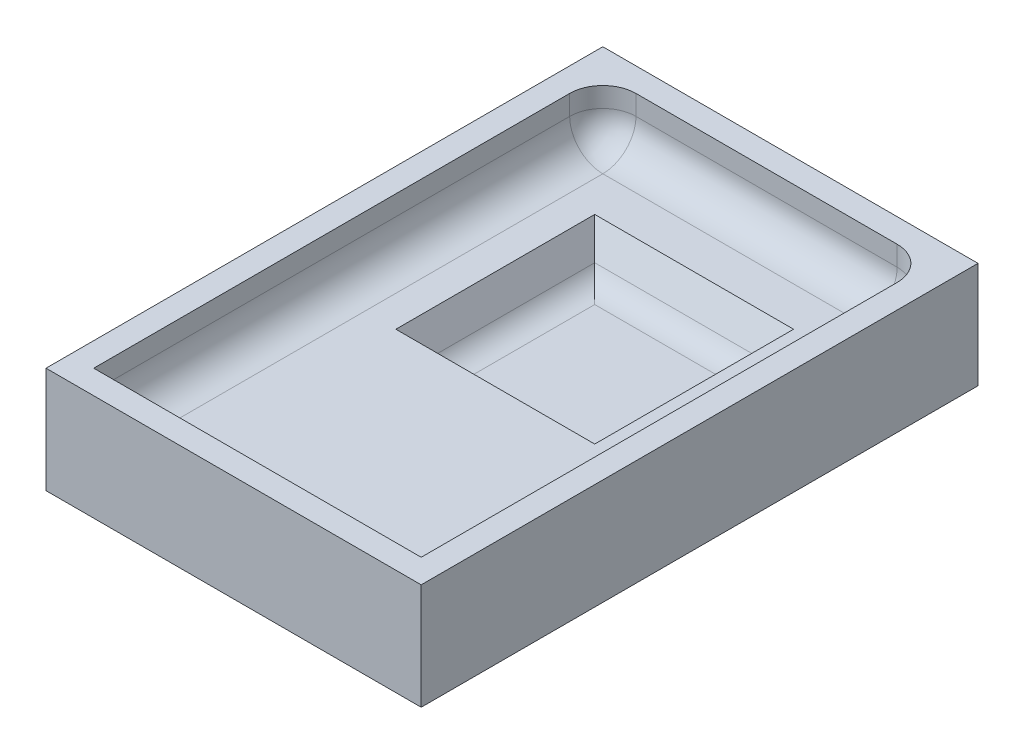
SolidWorks part; units mm, degrees
ref_plane "Front Plane" through (0, 0, 0) normal (0, 0, 1) x (1, 0, 0)
ref_plane "Top Plane" through (0, 0, 0) normal (0, 1, 0) x (1, 0, 0)
ref_plane "Right Plane" through (0, 0, 0) normal (1, 0, 0) x (0, 0, -1)
sketch "Sketch1" plane through (0, 0, 0) normal (0, 1, 0) x (1, 0, 0)
  line L1 (0, 0) -> (28.3, 0)
  line L2 (0, 0) -> (0, 42)
  line L3 (0, 42) -> (28.3, 42)
  line L4 (28.3, 0) -> (28.3, 42)
  dimension "D1" = 28.3
  dimension "D2" = 42
extrude "Boss-Extrude1" add sketch "Sketch1" along normal blind 4
sketch "Sketch2" plane through (0, 4, 0) normal (0, 1, 0) x (1, 0, 0)
  line L0 (28.3, 42) -> (0, 42) construction
  line L1 (6.65, 34.74) -> (21.65, 34.74)
  line L2 (6.65, 34.74) -> (6.65, 19.74)
  line L3 (6.65, 19.74) -> (21.65, 19.74)
  line L4 (21.65, 34.74) -> (21.65, 19.74)
  point P7 (14.15, 42)
  point P8 (14.15, 34.74)
  dimension "D1" = 15
  dimension "D2" = 7.26
extrude "Cut-Extrude1" cut sketch "Sketch2" against normal blind 3
draft "Draft1" type of draft neutral plane draft angle 30 faces to draft 4 face at (6.65, 2.5, -27.24) face at (14.15, 2.5, -19.74) face at (21.65, 2.5, -27.24) face at (14.15, 2.5, -34.74) neutral plane through (0, 4, 0) neutral plane normal (0, 1, 0) parameters "D1"=30
fillet "Fillet1" radius 2 4 edges at (14.15, 1, -33.0079) (19.9179, 1, -27.24) (14.15, 1, -21.4721) (8.3821, 1, -27.24)
sketch "Sketch4" plane through (0, 4, 0) normal (0, 1, 0) x (1, 0, 0)
  line L1 (0, 42) -> (28.3, 42)
  line L2 (0, 42) -> (0, 0)
  line L3 (0, 0) -> (28.3, 0)
  line L4 (28.3, 42) -> (28.3, 0)
  line L5 (1.8, 40.2) -> (26.5, 40.2)
  line L6 (1.8, 40.2) -> (1.8, 1.8)
  line L7 (1.8, 1.8) -> (26.5, 1.8)
  line L8 (26.5, 40.2) -> (26.5, 1.8)
  point P10 (26.5, 21)
  point P11 (28.3, 21)
  point P12 (14.15, 42)
  point P13 (14.15, 40.2)
  dimension "D1" = 1.8
  dimension "D2" = 1.8
extrude "Boss-Extrude2" add sketch "Sketch4" along normal blind 4
fillet "Fillet2" radius 2.5 5 edges at (26.5, 4, -21) (26.5, 6, -40.2) (1.8, 6, -40.2) (14.15, 4, -40.2) (1.8, 4, -21)
